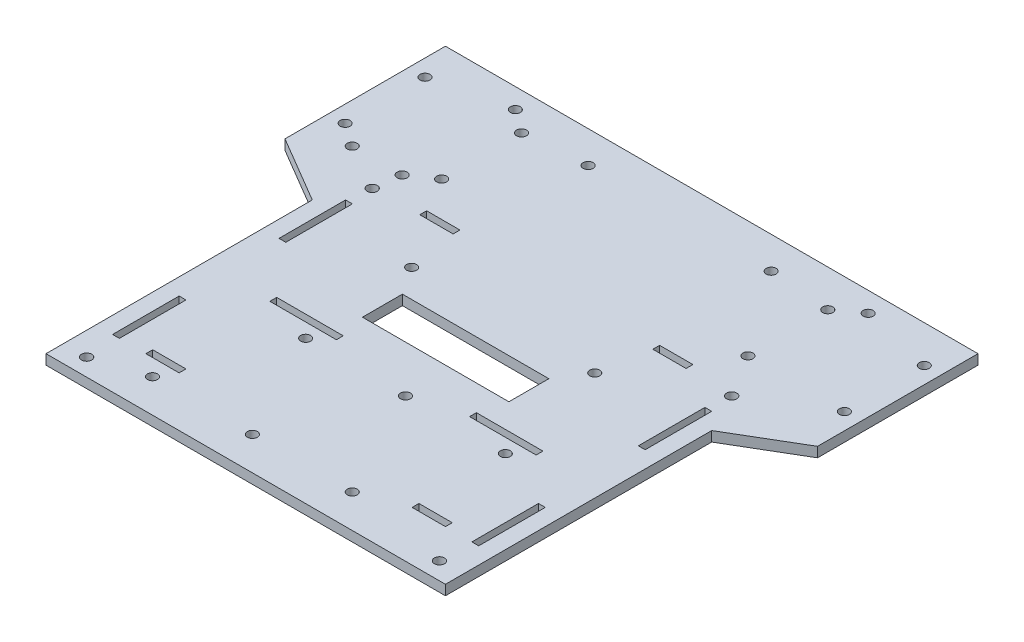
SolidWorks part; units mm, degrees
ref_plane "Front Plane" through (0, 0, 0) normal (0, 0, 1) x (1, 0, 0)
ref_plane "Top Plane" through (0, 0, 0) normal (0, 1, 0) x (1, 0, 0)
ref_plane "Right Plane" through (0, 0, 0) normal (1, 0, 0) x (0, 0, -1)
sketch "Sketch1" plane through (0, 0, 0) normal (0, 1, 0) x (1, 0, 0)
  line L0 (-60, 10) -> (-80, 21.7918)
  line L1 (60, -70) -> (-60, -70)
  line L2 (60, -70) -> (60, 70)
  line L3 (60, 70) -> (-60, 70)
  line L4 (-60, -70) -> (-60, 70)
  line L5 (60, -70) -> (-60, 70) construction
  line L6 (60, 70) -> (-60, -70) construction
  line L7 (-80, 21.7918) -> (-80, 70)
  line L8 (-80, 70) -> (-60, 70)
  line L9 (0, 0) -> (0, 70) construction
  line L10 (60, 10) -> (80, 21.7918)
  line L11 (80, 70) -> (60, 70)
  line L12 (80, 21.7918) -> (80, 70)
  point P0 (0, 0)
  dimension "D1" = 140
  dimension "D2" = 120
  dimension "D3" = 20
  dimension "D4" = 30.523
  dimension "D5" = 60
extrude "Boss-Extrude1" add sketch "Sketch1" along normal blind 3 contours L4 L1 L2 L3 | L8 L7 L0 L4 | L10 L12 L11 L2
sketch "Sketch2" plane through (0, 3, 0) normal (0, 1, 0) x (1, 0, 0)
  line L2 (0, 0) -> (0, -70) construction
  line L3 (60, -70) -> (-60, -70) construction
  circle A0 centre (-38, -60) radius 1.5
  circle A1 centre (-25, -27) radius 1.5
  circle A2 centre (5, -27) radius 1.5
  circle A3 centre (-8, -60) radius 1.5
  circle A4 centre (35, -27) radius 1.5
  circle A5 centre (22, -60) radius 1.5
  dimension "D1" = 3
  dimension "D2" = 38
  dimension "D3" = 10
  dimension "D4" = 3
  dimension "D6" = 33
  dimension "D5" = 13
  dimension "D7" = 3
extrude "Cut-Extrude1" cut sketch "Sketch2" against normal through all
sketch "Sketch3" plane through (0, 3, 0) normal (0, 1, 0) x (1, 0, 0)
  line L0 (-0.0296, 57.8856) -> (-0.0296, -0.1144) construction
  line L1 (-30.0296, 33.8856) -> (29.9704, 33.8856) construction
  line L4 (-80, 21.7918) -> (-80, 70) construction
  line L6 (-80, 21.7918) -> (-80, 70) construction
  line L7 (80, 70) -> (-80, 70) construction
  line L8 (-60, 10) -> (-60, 70) construction
  line L9 (60, 10) -> (60, 70) construction
  circle A0 centre (-27.5296, 60.3856) radius 1.5
  circle A1 centre (-27.5296, 7.3856) radius 1.5
  circle A2 centre (27.4704, 7.3856) radius 1.5
  circle A3 centre (27.4704, 60.3856) radius 1.5
  point P16 (-80, 45.8959)
  dimension "D1" = 52.4704
  dimension "D2" = 36.1144
  dimension "D3" = 3
  dimension "D4" = 79.9704
  dimension "D5" = 26.5
extrude "Cut-Extrude3" cut sketch "Sketch3" against normal through all
sketch "Sketch4" plane through (0, 3, 0) normal (0, 1, 0) x (1, 0, 0)
  line L0 (-60.5, 58.8639) -> (-60.5, 32.8639) construction
  line L1 (-80, 21.7918) -> (-80, 70) construction
  line L2 (80, 70) -> (-80, 70) construction
  line L3 (0, 0) -> (0, 70) construction
  circle A0 centre (-75, 34.8639) radius 1.5
  circle A1 centre (-75, 58.8639) radius 1.5
  circle A2 centre (-46, 34.8639) radius 1.5
  circle A3 centre (-46, 58.8639) radius 1.5
  circle A4 centre (46, 58.8639) radius 1.5
  circle A5 centre (46, 34.8639) radius 1.5
  circle A6 centre (75, 34.8639) radius 1.5
  circle A7 centre (75, 58.8639) radius 1.5
  dimension "D1" = 3
  dimension "D2" = 3
  dimension "D5" = 5
  dimension "D6" = 11.1361
  dimension "D7" = 5
  dimension "D3" = 24
  dimension "D4" = 14.5
extrude "Cut-Extrude4" cut sketch "Sketch4" against normal through all
sketch "Sketch5" plane through (0, 3, 0) normal (0, 1, 0) x (1, 0, 0)
  line L0 (80, 70) -> (-80, 70) construction
  line L1 (-80, 21.7918) -> (-80, 70) construction
  circle A0 centre (-68, 30) radius 1.5
  circle A1 centre (-53, 30) radius 1.5
  dimension "D1" = 3
  dimension "D2" = 3
  dimension "D3" = 40
  dimension "D4" = 40
  dimension "D6" = 12
  dimension "D5" = 15
extrude "Cut-Extrude5" cut sketch "Sketch5" against normal blind 3
sketch "Sketch6" plane through (0, 3, 0) normal (0, 1, 0) x (1, 0, 0)
  line L0 (60, -70) -> (-60, -70) construction
  line L1 (-45, -52.95) -> (-35, -52.95)
  line L2 (-45, -52.95) -> (-45, -55)
  line L3 (-45, -55) -> (-35, -55)
  line L4 (-35, -52.95) -> (-35, -55)
  line L5 (-45, -52.95) -> (-35, -55) construction
  line L6 (-45, -55) -> (-35, -52.95) construction
  line L7 (-60, -70) -> (-60, 10) construction
  line L8 (0, 0) -> (0, -70) construction
  line L9 (35, -52.95) -> (35, -55)
  line L10 (45, -55) -> (35, -55)
  line L11 (45, -52.95) -> (45, -55)
  line L12 (45, -52.95) -> (35, -52.95)
  line L13 (20, -22.75) -> (20, -20.7)
  line L14 (-20, -22.75) -> (-40, -22.75)
  line L15 (-20, -22.75) -> (-20, -20.7)
  line L16 (-20, -20.7) -> (-40, -20.7)
  line L17 (-40, -22.75) -> (-40, -20.7)
  line L18 (-20, -22.75) -> (-40, -20.7) construction
  line L19 (-20, -20.7) -> (-40, -22.75) construction
  line L20 (20, -22.75) -> (40, -22.75)
  line L21 (40, -22.75) -> (40, -20.7)
  line L22 (20, -20.7) -> (40, -20.7)
  line L23 (-60, -30) -> (60, -30) construction
  line L24 (60, -70) -> (60, 10) construction
  line L25 (-30, -21.725) -> (60, -21.725) construction
  line L26 (30, 24.35) -> (30, 22.3)
  line L27 (-40, 24.35) -> (-30, 24.35)
  line L28 (-40, 24.35) -> (-40, 22.3)
  line L29 (-40, 22.3) -> (-30, 22.3)
  line L30 (-30, 24.35) -> (-30, 22.3)
  line L31 (-40, 24.35) -> (-30, 22.3) construction
  line L32 (-40, 22.3) -> (-30, 24.35) construction
  line L33 (40, 24.35) -> (40, 22.3)
  line L34 (40, 24.35) -> (30, 24.35)
  line L35 (40, 22.3) -> (30, 22.3)
  circle A0 centre (-53, -64.8) radius 1.525
  circle A1 centre (53, -64.8) radius 1.525
  point P0 (-40, -53.975)
  point P16 (-30, -21.725)
  point P31 (-35, 23.325)
  dimension "D9" = 7
  dimension "D11" = 3.05
  dimension "D1" = 2.05
  dimension "D2" = 15
  dimension "D3" = 15
  dimension "D4" = 10
  dimension "D5" = 2.05
  dimension "D6" = 30.2
  dimension "D7" = 20
  dimension "D8" = 20
  dimension "D10" = 5.2
  dimension "D12" = 10
  dimension "D13" = 5
  dimension "D14" = 2.05
  dimension "D15" = 43
extrude "Cut-Extrude7" cut sketch "Sketch6" against normal through all
sketch "Sketch9" plane through (0, 3, 0) normal (0, 1, 0) x (1, 0, 0)
  line L0 (80, 70) -> (-80, 70) construction
  line L1 (-80, 21.7918) -> (-80, 70) construction
  line L2 (0, 0) -> (0, 70) construction
  circle A0 centre (-54, 22) radius 1.525
  circle A2 centre (54, 22) radius 1.525
  dimension "D1" = 3.05
  dimension "D2" = 48
  dimension "D3" = 26
extrude "Cut-Extrude8" cut sketch "Sketch9" against normal blind 3
sketch "Sketch10" plane through (0, 3, 0) normal (0, 1, 0) x (1, 0, 0)
  line L0 (60, -70) -> (60, 10) construction
  line L1 (22.0465, -12.9751) -> (-21.9535, -12.9751)
  line L2 (22.0465, -12.9751) -> (22.0465, -0.9751)
  line L3 (22.0465, -0.9751) -> (-21.9535, -0.9751)
  line L4 (-21.9535, -12.9751) -> (-21.9535, -0.9751)
  line L5 (22.0465, -12.9751) -> (-21.9535, -0.9751) construction
  line L6 (22.0465, -0.9751) -> (-21.9535, -12.9751) construction
  line L7 (80, 70) -> (-80, 70) construction
  point P0 (0.0465, -6.9751)
  dimension "D1" = 12
  dimension "D2" = 44
  dimension "D3" = 37.9535
  dimension "D4" = 70.9751
extrude "Cut-Extrude9" cut sketch "Sketch10" against normal blind 5
sketch "Sketch11" plane through (0, 3, 0) normal (0, 1, 0) x (1, 0, 0)
  line L0 (80, 70) -> (-80, 70) construction
  line L1 (0, 0) -> (0, 70) construction
  line L2 (-80, 21.7918) -> (-80, 70) construction
  circle A0 centre (-53, 64) radius 1.5
  circle A1 centre (53, 64) radius 1.5
  dimension "D1" = 3
  dimension "D3" = 27
  dimension "D2" = 6
extrude "Cut-Extrude10" cut sketch "Sketch11" against normal blind 5
sketch "Sketch12" plane through (0, 3, 0) normal (0, 1, 0) x (1, 0, 0)
  line L0 (80, 70) -> (-80, 70) construction
  line L1 (-55, 15) -> (-52.95, 15)
  line L2 (-55, 15) -> (-55, -5)
  line L3 (-55, -5) -> (-52.95, -5)
  line L4 (-52.95, 15) -> (-52.95, -5)
  line L5 (-55, 15) -> (-52.95, -5) construction
  line L6 (-55, -5) -> (-52.95, 15) construction
  line L7 (-52.95, -55) -> (-55, -55)
  line L8 (-52.95, -55) -> (-52.95, -35)
  line L9 (-52.95, -35) -> (-55, -35)
  line L10 (-55, -55) -> (-55, -35)
  line L11 (-52.95, -55) -> (-55, -35) construction
  line L12 (-52.95, -35) -> (-55, -55) construction
  line L13 (-60, -70) -> (-60, 10) construction
  line L14 (60, -70) -> (-60, -70) construction
  line L15 (0, 0) -> (0, -70) construction
  line L16 (52.95, -55) -> (55, -55)
  line L17 (52.95, -55) -> (52.95, -35)
  line L18 (55, -55) -> (55, -35)
  line L19 (52.95, -35) -> (55, -35)
  line L20 (52.95, 15) -> (52.95, -5)
  line L21 (55, -5) -> (52.95, -5)
  line L22 (55, 15) -> (55, -5)
  line L23 (55, 15) -> (52.95, 15)
  point P0 (-53.975, 5)
  point P5 (-53.975, -45)
  dimension "D1" = 20
  dimension "D2" = 55
  dimension "D3" = 2.05
  dimension "D4" = 5
  dimension "D5" = 2.05
  dimension "D6" = 20
  dimension "D7" = 5
  dimension "D8" = 15
extrude "Cut-Extrude11" cut sketch "Sketch12" against normal blind 10
